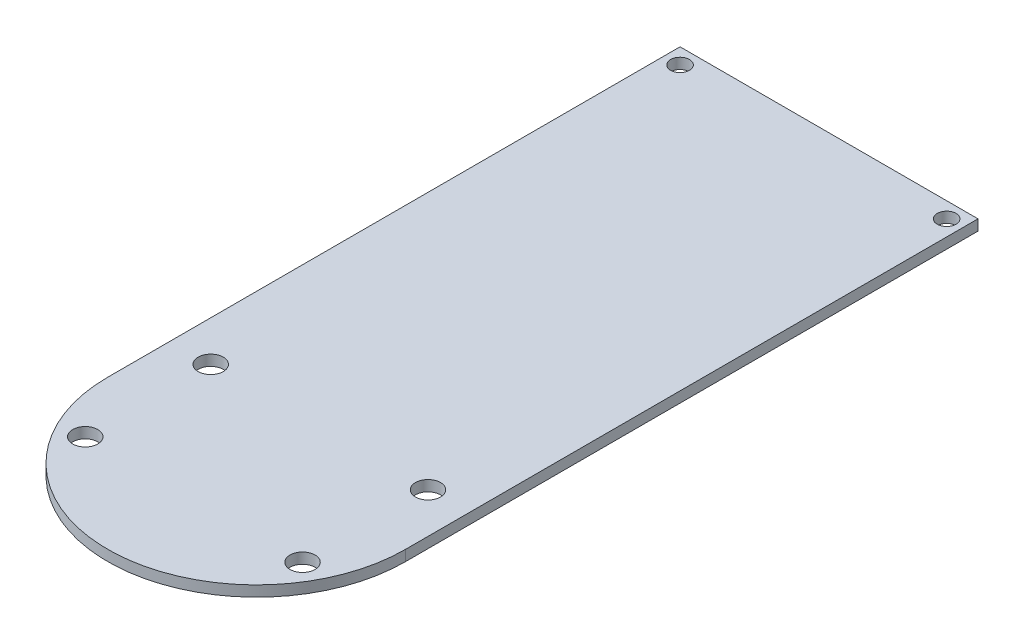
SolidWorks part; units mm, degrees
ref_plane "Plano frontal" through (0, 0, 0) normal (0, 0, 1) x (1, 0, 0)
ref_plane "Plano superior" through (0, 0, 0) normal (0, 1, 0) x (1, 0, 0)
ref_plane "Plano direito" through (0, 0, 0) normal (1, 0, 0) x (0, 0, -1)
sketch "Esboço1" plane through (0, 0, 0) normal (0, 1, 0) x (1, 0, 0)
  line L0 (-23.75, 45.625) -> (23.75, -45.625) construction
  line L1 (-23.75, 45.625) -> (23.75, 45.625)
  line L2 (-23.75, 45.625) -> (-23.75, -45.625)
  line L4 (23.75, 45.625) -> (23.75, -45.625)
  line L5 (-23.75, -45.625) -> (23.75, 45.625) construction
  line L6 (0, 45.625) -> (0, 0) construction
  arc A0 (-23.75, -45.625) -> (23.75, -45.625) centre (0, -45.625) ccw
  circle A1 centre (0, -45.625) radius 20 construction
  circle A2 centre (0, -25.625) radius 2 construction
  circle A6 centre (-21.25, 43.125) radius 1.5
  circle A7 centre (21.25, 43.125) radius 1.5
  circle A8 centre (17.3205, -35.625) radius 2
  circle A9 centre (17.3205, -55.625) radius 2
  circle A10 centre (0, -65.625) radius 2 construction
  circle A11 centre (-17.3205, -55.625) radius 2
  circle A12 centre (-17.3205, -35.625) radius 2
  point P1 (0, 0)
  point P18 (0, -45.625)
  point P29 (0, -45.625)
  dimension "D3" = 4
  dimension "D5" = 40
  dimension "D6" = 3
  dimension "D7" = 2.5
  dimension "D1" = 47.5
  dimension "D2" = 91.25
  dimension "D8" = 2.5
  dimension "D4" = 6
extrude "Ressalto-extrusão1" add sketch "Esboço1" along normal blind 1.7
sketch "Esboço2" plane through (0, 0, 0) normal (0, -1, 0) x (1, 0, 0)
  line L0 (0, 0) -> (0, 46.25) construction
  line L2 (-2.15, 43.665) -> (2.15, 43.665)
  line L3 (-2.15, 43.665) -> (-2.15, 48.835)
  line L4 (-2.15, 48.835) -> (2.15, 48.835)
  line L5 (2.15, 43.665) -> (2.15, 48.835)
  line L6 (-2.15, 43.665) -> (2.15, 48.835) construction
  line L7 (-2.15, 48.835) -> (2.15, 43.665) construction
  dimension "D1" = 46.25
  dimension "D2" = 5.17
  dimension "D3" = 4.3
extrude "Ressalto-extrusão2" add sketch "Esboço2" along normal blind 0.9
chamfer "Chanfro1" distance 0.7 angle 45 2 edges at (2.15, 0, 46.25) (-2.15, 0, 46.25)
